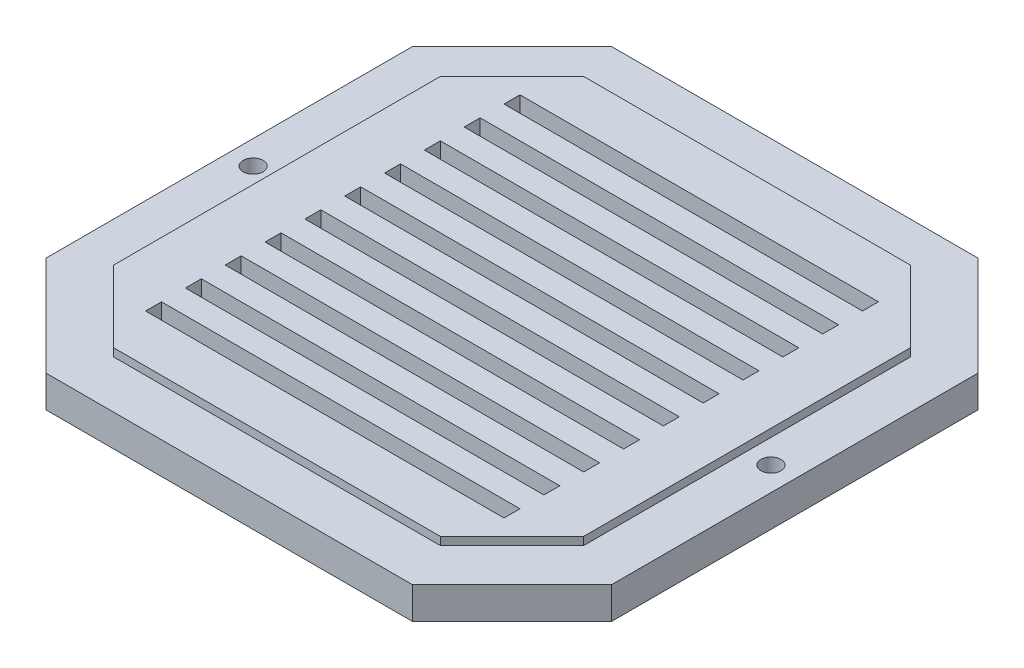
SolidWorks part; units mm, degrees
ref_plane "Front Plane" through (0, 0, 0) normal (0, 0, 1) x (1, 0, 0)
ref_plane "Top Plane" through (0, 0, 0) normal (0, 1, 0) x (1, 0, 0)
ref_plane "Right Plane" through (0, 0, 0) normal (1, 0, 0) x (0, 0, -1)
sketch "Sketch1" plane through (0, 0, 0) normal (0, 1, 0) x (1, 0, 0)
  line L0 (-35.5, 23) -> (-23, 35.5)
  line L1 (-23, -35.5) -> (23, -35.5)
  line L2 (-35.5, -23) -> (-35.5, 23)
  line L3 (-23, 35.5) -> (23, 35.5)
  line L4 (35.5, -23) -> (35.5, 23)
  line L5 (-35.5, -35.5) -> (35.5, 35.5) construction
  line L6 (-35.5, 35.5) -> (35.5, -35.5) construction
  line L7 (23, -35.5) -> (35.5, -23)
  line L8 (-23, -35.5) -> (-35.5, -23)
  line L9 (23, 35.5) -> (35.5, 23)
  point P0 (0, 0)
  dimension "D1" = 71
  dimension "D2" = 71
extrude "Boss-Extrude1" add sketch "Sketch1" along normal blind 4
sketch "Sketch3" plane through (0, 0, 0) normal (0, 1, 0) x (1, 0, 0)
  line L16 (-29.5, 20.5147) -> (-20.5147, 29.5)
  line L17 (-20.5147, 29.5) -> (20.5147, 29.5)
  line L18 (20.5147, 29.5) -> (29.5, 20.5147)
  line L19 (29.5, -20.5147) -> (29.5, 20.5147)
  line L20 (20.5147, -29.5) -> (29.5, -20.5147)
  line L21 (-20.5147, -29.5) -> (20.5147, -29.5)
  line L22 (-20.5147, -29.5) -> (-29.5, -20.5147)
  line L23 (-29.5, -20.5147) -> (-29.5, 20.5147)
  line L24 (-35.5, 23) -> (-35.5, -23) construction
  line L25 (23, 35.5) -> (-23, 35.5) construction
  line L26 (35.5, -23) -> (35.5, 23) construction
  line L27 (35.5, 23) -> (23, 35.5) construction
  line L28 (23, -35.5) -> (35.5, -23) construction
  line L29 (-23, -35.5) -> (23, -35.5) construction
  line L30 (-35.5, -23) -> (-23, -35.5) construction
  line L31 (-23, 35.5) -> (-35.5, 23) construction
  dimension "D1" = 6
  dimension "D2" = 6
  dimension "D3" = 6
  dimension "D4" = 6
  dimension "D5" = 6
  dimension "D6" = 6
  dimension "D7" = 6
  dimension "D8" = 6
extrude "Boss-Extrude3" add sketch "Sketch3" along normal blind 1 from surface at 4 starting at face at (0, 4, 0)
sketch "Sketch5" plane through (0, 4, 0) normal (0, 1, 0) x (1, 0, 0)
  line L0 (35.5, -23) -> (35.5, 23) construction
  line L2 (0, 44.0655) -> (0, -46.2743) construction
  line L3 (-40.5476, 0) -> (58.6591, 0) construction
  circle A0 centre (32.5, 0) radius 1.25
  circle A4 centre (-32.5, 0) radius 1.25
  dimension "D1" = 2.5
  dimension "D2" = 0
  dimension "D3" = 3
extrude "Cut-Extrude2" cut sketch "Sketch5" against normal up to next
sketch "Sketch6" plane through (0, 0, 0) normal (0, -1, 0) x (1, 0, 0)
  line L0 (0, 0) -> (0, -21.5582) construction
  circle A1 centre (32.5, 0) radius 2.25
  circle A2 centre (-32.5, 0) radius 2.25
  dimension "D1" = 4.5
extrude "Cut-Extrude3" cut sketch "Sketch6" against normal blind 2
sketch "Sketch7" plane through (0, 0, 0) normal (0, -1, 0) x (1, 0, 0)
  line L0 (0, 9.4766) -> (0, -10.1054) construction
  line L1 (-22.5, 21.5) -> (22.5, 21.5)
  line L2 (-22.5, 21.5) -> (-22.5, 23.5)
  line L3 (-22.5, 23.5) -> (22.5, 23.5)
  line L4 (22.5, 21.5) -> (22.5, 23.5)
  line L5 (-22.5, 21.5) -> (22.5, 23.5) construction
  line L6 (-22.5, 23.5) -> (22.5, 21.5) construction
  line L7 (-13.8579, 0) -> (16.5032, 0) construction
  line L8 (-22.5, 16.5) -> (-22.5, 18.5)
  line L9 (-22.5, 16.5) -> (22.5, 16.5)
  line L10 (22.5, 16.5) -> (22.5, 18.5)
  line L11 (-22.5, 18.5) -> (22.5, 18.5)
  line L12 (-22.5, 11.5) -> (-22.5, 13.5)
  line L13 (-22.5, 11.5) -> (22.5, 11.5)
  line L14 (22.5, 11.5) -> (22.5, 13.5)
  line L15 (-22.5, 13.5) -> (22.5, 13.5)
  line L16 (-22.5, 6.5) -> (-22.5, 8.5)
  line L17 (-22.5, 6.5) -> (22.5, 6.5)
  line L18 (22.5, 6.5) -> (22.5, 8.5)
  line L19 (-22.5, 8.5) -> (22.5, 8.5)
  line L20 (-22.5, 1.5) -> (-22.5, 3.5)
  line L21 (-22.5, 1.5) -> (22.5, 1.5)
  line L22 (22.5, 1.5) -> (22.5, 3.5)
  line L23 (-22.5, 3.5) -> (22.5, 3.5)
  line L24 (-22.5, -3.5) -> (-22.5, -1.5)
  line L25 (-22.5, -3.5) -> (22.5, -3.5)
  line L26 (22.5, -3.5) -> (22.5, -1.5)
  line L27 (-22.5, -1.5) -> (22.5, -1.5)
  line L28 (-22.5, -8.5) -> (-22.5, -6.5)
  line L29 (-22.5, -8.5) -> (22.5, -8.5)
  line L30 (22.5, -8.5) -> (22.5, -6.5)
  line L31 (-22.5, -6.5) -> (22.5, -6.5)
  line L32 (-22.5, -13.5) -> (-22.5, -11.5)
  line L33 (-22.5, -13.5) -> (22.5, -13.5)
  line L34 (22.5, -13.5) -> (22.5, -11.5)
  line L35 (-22.5, -11.5) -> (22.5, -11.5)
  line L36 (-22.5, -18.5) -> (-22.5, -16.5)
  line L37 (-22.5, -18.5) -> (22.5, -18.5)
  line L38 (22.5, -18.5) -> (22.5, -16.5)
  line L39 (-22.5, -16.5) -> (22.5, -16.5)
  line L40 (-22.5, -23.5) -> (-22.5, -21.5)
  line L41 (-22.5, -23.5) -> (22.5, -23.5)
  line L42 (22.5, -23.5) -> (22.5, -21.5)
  line L43 (-22.5, -21.5) -> (22.5, -21.5)
  point P0 (0, 22.5)
  dimension "D1" = 2
  dimension "D2" = 45
  dimension "D3" = 21.5
  dimension "D4" = 10
extrude "Cut-Extrude4" cut sketch "Sketch7" against normal blind 10
